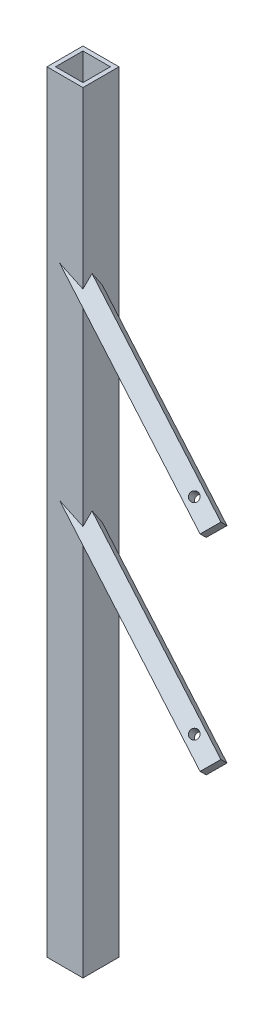
SolidWorks part; units mm, degrees
ref_plane "Front Plane" through (0, 0, 0) normal (0, 0, 1) x (1, 0, 0)
ref_plane "Top Plane" through (0, 0, 0) normal (0, 1, 0) x (1, 0, 0)
ref_plane "Right Plane" through (0, 0, 0) normal (1, 0, 0) x (0, 0, -1)
sketch "Sketch2" plane through (0, 0, 0) normal (0, 1, 0) x (1, 0, 0)
  line L1 (-10.5, 10.5) -> (10.5, 10.5)
  line L2 (-10.5, 10.5) -> (-10.5, -10.5)
  line L3 (-10.5, -10.5) -> (10.5, -10.5)
  line L4 (10.5, 10.5) -> (10.5, -10.5)
  line L5 (-10.5, 10.5) -> (10.5, -10.5) construction
  line L6 (-10.5, -10.5) -> (10.5, 10.5) construction
  point P0 (0, 0)
  dimension "D1" = 21
  dimension "D2" = 21
extrude "Boss-Extrude1" add sketch "Sketch2" along normal blind 250 and the other way blind 200
sketch "Sketch3" plane through (0, -200, 0) normal (0, -1, 0) x (1, 0, 0)
  line L1 (-8, 8) -> (8, 8)
  line L2 (-8, 8) -> (-8, -8)
  line L3 (-8, -8) -> (8, -8)
  line L4 (8, 8) -> (8, -8)
  line L5 (-8, 8) -> (8, -8) construction
  line L6 (-8, -8) -> (8, 8) construction
  point P0 (0, 0)
extrude "Cut-Extrude1" cut sketch "Sketch3" against normal blind 800
sketch "Sketch7" plane through (10.5, 0, 0) normal (1, 0, 0) x (0, 0, -1)
  line L0 (-10.5, 28.157) -> (10.5, 49.157)
  line L1 (-10.5, 250) -> (-10.5, -200) construction
  line L2 (10.5, 250) -> (10.5, -200) construction
sketch "Sketch8" plane through (0, 0, -10.5) normal (0, 0, -1) x (-1, 0, 0)
  line L0 (-10.5, 49.1574) -> (3.0946, 55.4967)
  line L1 (-10.5, 250) -> (-10.5, -200) construction
sketch "Sketch9" plane through (0, 0, 10.5) normal (0, 0, 1) x (1, 0, 0)
  line L0 (10.5, 28.157) -> (-3.0946, 34.4963)
ref_plane "Plane1" through (9.1588, 19.6412, 19.6412) normal (0.3131, 0.6715, 0.6715) x (0.9497, -0.2214, -0.2214)
sketch "Sketch14" plane through (9.1588, 19.6412, 19.6412) normal (0.3131, 0.6715, 0.6715) x (0.9497, -0.2214, -0.2214)
  line L0 (-12.9024, 16.9679) -> (98.0083, -50.8466)
  line L1 (98.0083, -50.8466) -> (103.2248, -42.3151)
  line L2 (103.2248, -42.3151) -> (-7.6859, 25.4995)
  line L3 (-7.6859, 25.4995) -> (-12.9024, 16.9679)
  circle A0 centre (87.8192, -38.7561) radius 2.5
  dimension "D3" = 5
  dimension "D4" = 5
  dimension "D5" = 15
  dimension "D1" = 130
  dimension "D2" = 10
  dimension "D6" = 130
extrude "Boss-Extrude3" add sketch "Sketch14" against normal blind 10
pattern_linear "LPattern1" count 2 spacing 120 along (0, 1, 0) of "Boss-Extrude3"
